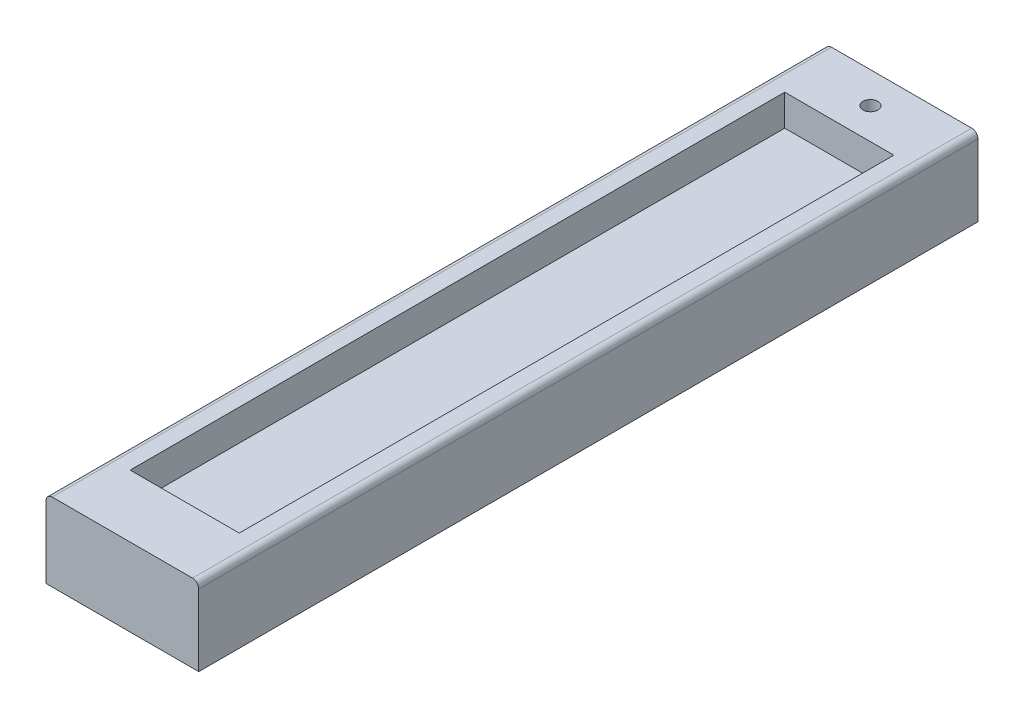
SolidWorks part; units mm, degrees
ref_plane "Front Plane" through (0, 0, 0) normal (0, 0, 1) x (1, 0, 0)
ref_plane "Top Plane" through (0, 0, 0) normal (0, 1, 0) x (1, 0, 0)
ref_plane "Right Plane" through (0, 0, 0) normal (1, 0, 0) x (0, 0, -1)
sketch "Sketch1" plane through (0, 0, 0) normal (0, 0, 1) x (1, 0, 0)
  line L1 (24.5, -10) -> (-24.5, -10)
  line L2 (24.5, -10) -> (24.5, 10)
  line L3 (24.5, 10) -> (-24.5, 10)
  line L4 (-24.5, -10) -> (-24.5, 10)
  line L5 (0, 10) -> (0, -10) construction
  line L6 (24.5, 0) -> (-24.5, 0) construction
  point P0 (0, 0)
  dimension "D1" = 20
  dimension "D2" = 49
extrude "Boss-Extrude1" add sketch "Sketch1" along normal mid plane 250
sketch "Sketch3" plane through (0, 10, 0) normal (0, 1, 0) x (1, 0, 0)
  line L0 (24.5, 125) -> (-24.5, 125) construction
  line L1 (24.5, 125) -> (-24.5, 125)
  line L2 (24.5, 125) -> (24.5, -125)
  line L3 (24.5, -125) -> (-24.5, -125)
  line L4 (-24.5, 125) -> (-24.5, -125)
  line L5 (0, -125) -> (0, 125) construction
  line L6 (24.5, 0) -> (-24.5, 0) construction
  point P0 (0, 0)
  dimension "D1" = 49
extrude "Boss-Extrude2" add sketch "Sketch3" along normal blind 5
ref_plane "Plane1" through (0, 15, 0) normal (0, 1, 0) x (1, 0, 0)
sketch "Sketch2" plane through (0, 15, 0) normal (0, 1, 0) x (1, 0, 0)
  line L1 (24.5, 125) -> (-24.5, 125) construction
  circle A0 centre (0, 115) radius 2.4
  dimension "D1" = 4.8
  dimension "D2" = 10
extrude "Cut-Extrude1" cut sketch "Sketch2" against normal blind 10 and the other way through all
sketch "Sketch5" plane through (0, 15, 0) normal (0, 1, 0) x (1, 0, 0)
  line L1 (-17.5, -105) -> (17.5, -105)
  line L2 (-17.5, -105) -> (-17.5, 105)
  line L3 (-17.5, 105) -> (17.5, 105)
  line L4 (17.5, -105) -> (17.5, 105)
  line L5 (-17.5, -105) -> (17.5, 105) construction
  line L6 (-17.5, 105) -> (17.5, -105) construction
  point P0 (0, 0)
  dimension "D1" = 35
  dimension "D2" = 210
extrude "Cut-Extrude3" cut sketch "Sketch5" against normal blind 10
fillet "Fillet1" radius 2 2 edges at (-24.5, 15, 0) (24.5, 15, 0)
sketch "Sketch4" plane through (0, -10, 0) normal (0, -1, 0) x (1, 0, 0)
  line L0 (-24.5, 125) -> (24.5, 125) construction
  line L5 (24.5, 125) -> (24.5, -125) construction
  circle A0 centre (-0.5, 110) radius 7.874
  dimension "D2" = 15.748
  dimension "D1" = 15
  dimension "D3" = 25
extrude "Cut-Extrude2" cut sketch "Sketch4" against normal blind 10
